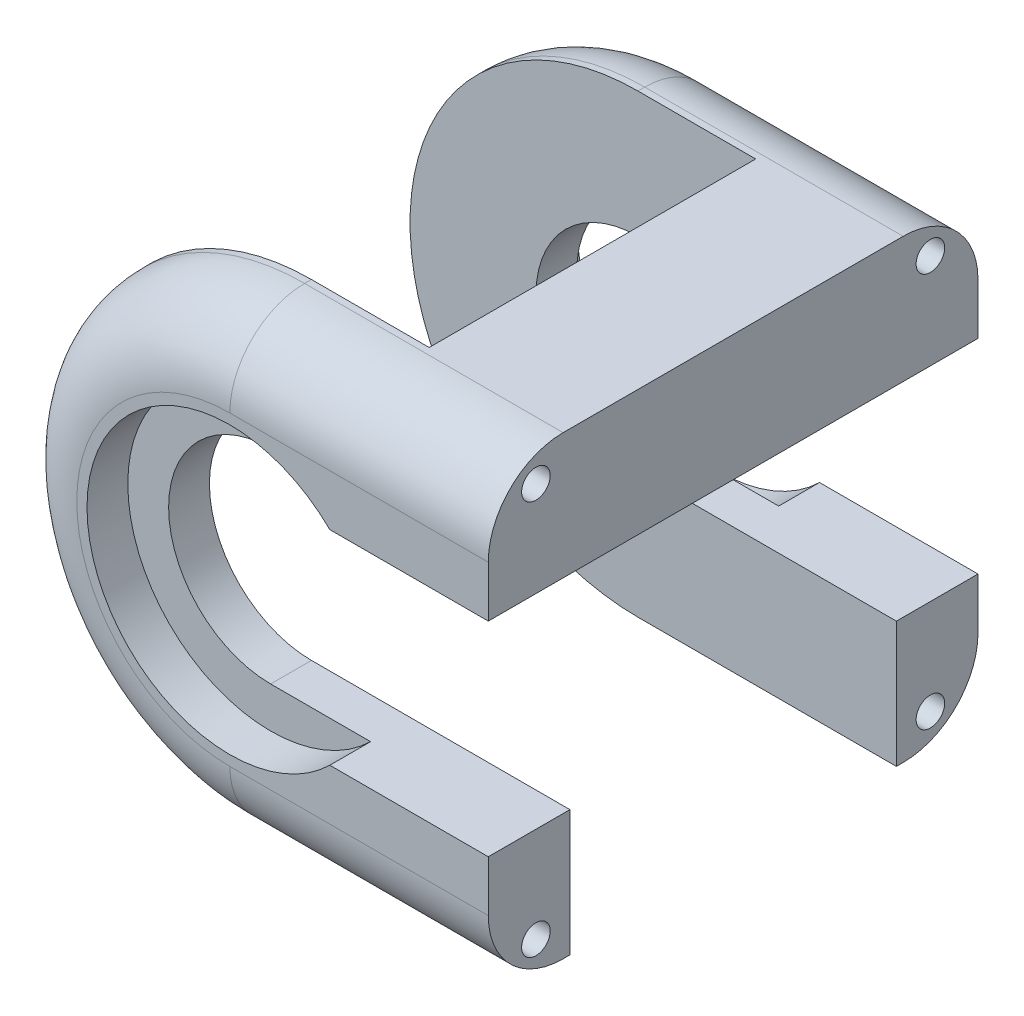
SolidWorks part; units mm, degrees
ref_plane "前视基准面" through (0, 0, 0) normal (0, 0, 1) x (1, 0, 0)
ref_plane "上视基准面" through (0, 0, 0) normal (0, 1, 0) x (1, 0, 0)
ref_plane "右视基准面" through (0, 0, 0) normal (1, 0, 0) x (0, 0, -1)
sketch "Sketch1" plane through (0, 0, 0) normal (0, 0, 1) x (1, 0, 0)
  line L0 (0, 0) -> (-38, 0)
  line L1 (-38, 0) -> (-38, 67)
  line L2 (-38, 67) -> (0, 67)
  line L3 (0, 67) -> (0, 0)
  arc A0 (-38, 67) -> (-38, 0) centre (-38, 33.5) ccw
  dimension "D1" = 38
  dimension "D2" = 67
extrude "Boss-Extrude1" add sketch "Sketch1" along normal blind 72 contours L3 L2 L1 L0 | L1 A0
sketch "Sketch2" plane through (0, 0, 0) normal (0, 0, -1) x (-1, 0, 0)
  circle A0 centre (38, 33.5) radius 21
extrude "Cut-Extrude1" cut sketch "Sketch2" against normal blind 6
sketch "Sketch3" plane through (0, 0, 72) normal (0, 0, 1) x (1, 0, 0)
  line L0 (-38, 0) -> (-38, 67) construction
  circle A0 centre (-38, 33.5) radius 21
extrude "Cut-Extrude2" cut sketch "Sketch3" against normal blind 6
sketch "Sketch4" plane through (0, 0, 0) normal (0, -1, 0) x (1, 0, 0)
  line L0 (-38, 0) -> (-71.5, 0) construction
  line L1 (-71.5, 72) -> (-71.5, 0) construction
  line L2 (-71.5, 60) -> (-20.6887, 60)
  line L3 (-71.5, 60) -> (-71.5, 12)
  line L4 (-71.5, 12) -> (-20.6887, 12)
  line L5 (-20.6887, 60) -> (-20.6887, 12)
  line L6 (-38, 72) -> (-71.5, 72) construction
  dimension "D1" = 12
  dimension "D2" = 12
extrude "Cut-Extrude3" cut sketch "Sketch4" against normal through all
sketch "Sketch6" plane through (0, 0, 0) normal (0, 0, -1) x (-1, 0, 0)
  circle A0 centre (38, 33.5) radius 15
extrude "Cut-Extrude4" cut sketch "Sketch6" against normal blind 200
sketch "Sketch7" plane through (0, 0, 0) normal (1, 0, 0) x (0, 0, -1)
  point P4 (-36, 33.5)
sketch "Sketch8" plane through (0, 0, 0) normal (1, 0, 0) x (0, 0, -1)
  line L0 (-72, 67) -> (0, 0) construction
  line L2 (-7, 4.5) -> (-65, 4.5) construction
  line L3 (-7, 4.5) -> (-7, 62.5) construction
  line L4 (-7, 62.5) -> (-65, 62.5) construction
  line L5 (-65, 4.5) -> (-65, 62.5) construction
  line L6 (-7, 4.5) -> (-65, 62.5) construction
  line L7 (-7, 62.5) -> (-65, 4.5) construction
  circle A0 centre (-65, 62.5) radius 2.5
  circle A1 centre (-7, 62.5) radius 2.5
  circle A2 centre (-7, 4.5) radius 2.5
  circle A3 centre (-65, 4.5) radius 2.5
  point P5 (-36, 33.5)
  dimension "D1" = 58
  dimension "D2" = 58
fillet "Fillet2" radius 11 6 edges at (-19, 0, 72) (-71.5, 33.5, 72) (-19, 0, 0) (-71.5, 33.5, 0) (-19, 67, 72) (-19, 67, 0)
sketch "Sketch10" plane through (0, 0, 0) normal (1, 0, 0) x (0, 0, -1)
  line L0 (-61, 0) -> (-11, 0) construction
  line L1 (-59.5, 0) -> (-12.5, 0)
  line L2 (-59.5, 0) -> (-59.5, 29.4068)
  line L3 (-59.5, 29.4068) -> (-12.5, 29.4068)
  line L4 (-12.5, 0) -> (-12.5, 29.4068)
  line L5 (-72, 54.5) -> (0, 54.5) construction
  point P6 (-36, 54.5)
  point P11 (-36, 0)
extrude "Cut-Extrude7" cut sketch "Sketch10" against normal blind 82
sketch "Sketch11" plane through (0, 0, 72) normal (0, 0, 1) x (1, 0, 0)
  line L0 (-38, 33.5) -> (0, 33.5)
  line L1 (0, 56) -> (0, 11) construction
  line L2 (-38, 48.5) -> (-38, 18.5)
  line L3 (-38, 18.5) -> (0, 18.5)
  line L4 (0, 18.5) -> (0, 48.5)
  line L5 (0, 48.5) -> (-38, 48.5)
  circle A1 centre (-38, 33.5) radius 15 construction
  circle M1 centre (-38, 33.5) radius 21
  line M4 (0, 11) -> (0, 56)
extrude "Cut-Extrude10" cut sketch "Sketch11" against normal up to next contours L5 L2 L0 M1 | L5 L0 M4 M1 | L3 L0 M1 M4 | L2 L3 L0 M1
hole_wizard "M5 Tapped Hole1" positions "3DSketch1" profile "Sketch12" tap size "M5" standard "GB"
sketch3d "3DSketch1"
  point P0 (0, 62.5, 65)
  point P3 (0, 62.5, 7)
  point P6 (0, 4.5, 7)
  point P9 (0, 4.5, 65)
sketch "Sketch12" plane through (0, 62.5, 65) normal (0, 1, 0) x (0, 0, -1)
  line L0 (0, 0) -> (0, 13.2618)
  line L1 (0, 13.2618) -> (2.1, 12)
  line L2 (2.1, 12) -> (2.1, 0)
  line L5 (2.1, 0) -> (0, 0)
  line L10 (0, 13.2618) -> (-2.1, 12) construction
  line L11 (0, -6.35) -> (0, 107.95) construction
  dimension "Tap Drill Dia." = 4.2
  dimension "Tap Drill Depth" = 12
  dimension "Drill Angle" = 118
cosmetic thread "Hole Thread1" parameters "D1"=10, "D2"=5
cosmetic thread "Hole Thread2" parameters "D1"=10, "D2"=5
cosmetic thread "Hole Thread3" parameters "D1"=10, "D2"=5
cosmetic thread "Hole Thread4" parameters "D1"=10, "D2"=5
sketch "Sketch13" plane through (-20.6887, 0, 0) normal (-1, 0, 0) x (0, 0, 1)
  line L1 (59.5, 18.5) -> (60, 18.5)
  line L2 (59.5, 18.5) -> (59.5, 0)
  line L3 (59.5, 0) -> (60, 0)
  line L4 (60, 18.5) -> (60, 0)
  line L5 (12.5, 18.5) -> (12, 18.5)
  line L6 (12.5, 18.5) -> (12.5, 0)
  line L7 (12.5, 0) -> (12, 0)
  line L8 (12, 18.5) -> (12, 0)
extrude "Cut-Extrude11" cut sketch "Sketch13" against normal through all
